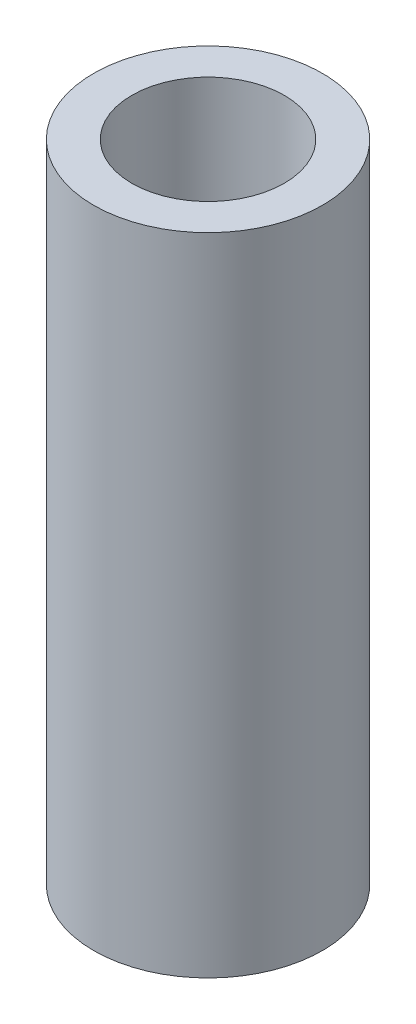
SolidWorks part; units mm, degrees
ref_plane "Front Plane" through (0, 0, 0) normal (0, 0, 1) x (1, 0, 0)
ref_plane "Top Plane" through (0, 0, 0) normal (0, 1, 0) x (1, 0, 0)
ref_plane "Right Plane" through (0, 0, 0) normal (1, 0, 0) x (0, 0, -1)
sketch "Sketch1" plane through (0, 0, 0) normal (0, 1, 0) x (1, 0, 0)
  circle A0 centre (0, 0) radius 4.5
  circle A1 centre (0, 0) radius 3
  dimension "D1" = 9
  dimension "D2" = 6
extrude "Boss-Extrude1" add sketch "Sketch1" along normal blind 25.4
